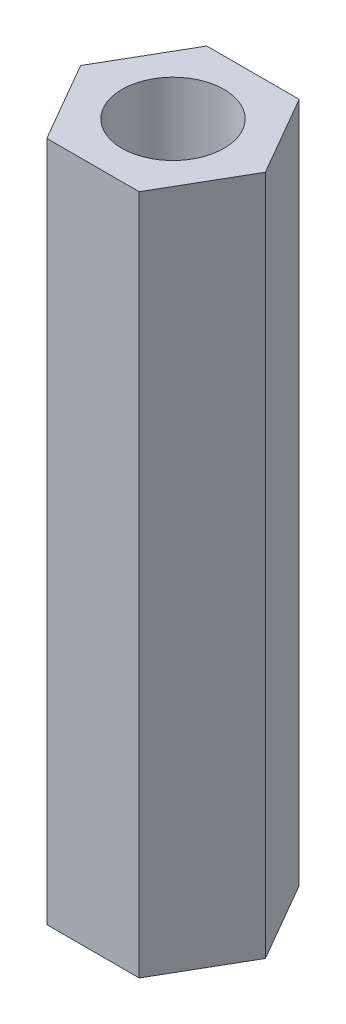
SolidWorks part; units mm, degrees
ref_plane "Front Plane" through (0, 0, 0) normal (0, 0, 1) x (1, 0, 0)
ref_plane "Top Plane" through (0, 0, 0) normal (0, 1, 0) x (1, 0, 0)
ref_plane "Right Plane" through (0, 0, 0) normal (1, 0, 0) x (0, 0, -1)
sketch "Sketch1" plane through (0, 0, 0) normal (0, 1, 0) x (1, 0, 0)
  line L1 (2.7135, 0) -> (1.3568, 2.35)
  line L2 (1.3568, 2.35) -> (-1.3568, 2.35)
  line L3 (-1.3568, 2.35) -> (-2.7135, 0)
  line L4 (-2.7135, 0) -> (-1.3568, -2.35)
  line L5 (-1.3568, -2.35) -> (1.3568, -2.35)
  line L6 (1.3568, -2.35) -> (2.7135, 0)
  circle A0 centre (0, 0) radius 2.35 construction
  circle A1 centre (0, 0) radius 1.5
  dimension "D1" = 4.7
extrude "Boss-Extrude1" add sketch "Sketch1" along normal blind 20
